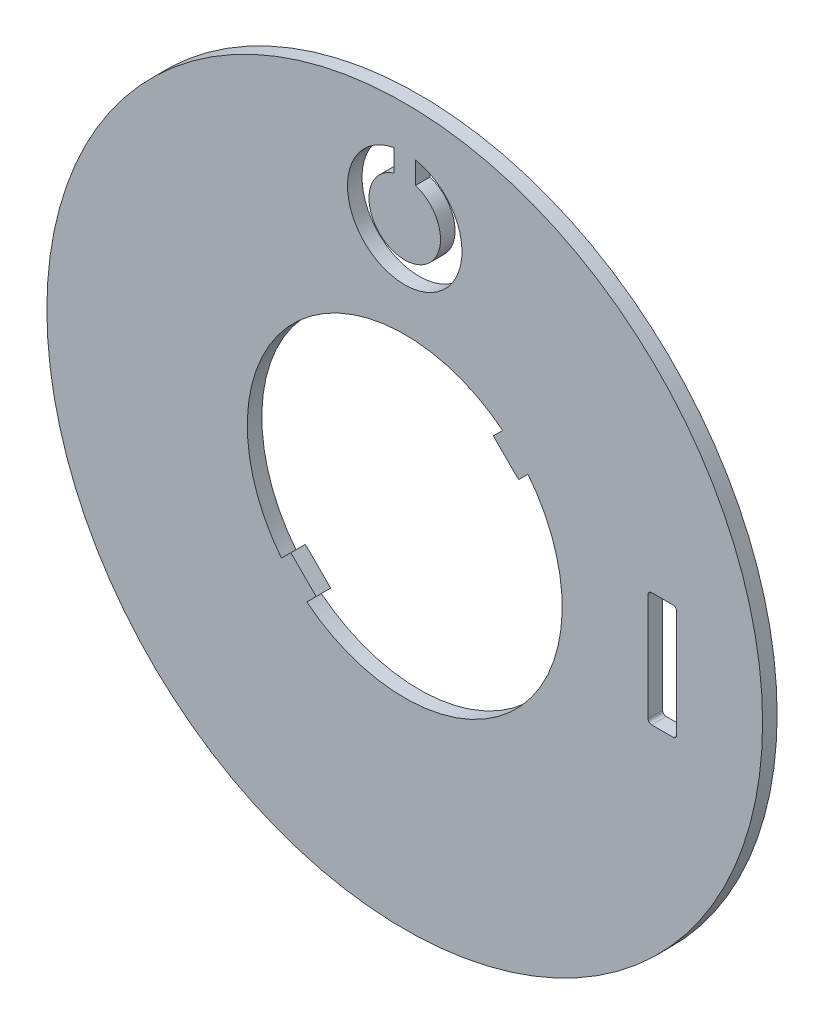
SolidWorks part; units mm, degrees
material "6061-T4 (SS)"
ref_plane "Front Plane" through (0, 0, 0) normal (0, 0, 1) x (1, 0, 0)
ref_plane "Top Plane" through (0, 0, 0) normal (0, 1, 0) x (1, 0, 0)
ref_plane "Right Plane" through (0, 0, 0) normal (1, 0, 0) x (0, 0, -1)
sketch "Sketch1" plane through (0, 0, 0) normal (0, 0, 1) x (1, 0, 0)
  line L4 (115.6621, 68.6943) -> (113.8943, 70.4621)
  line L5 (114.955, 67.9872) -> (115.6621, 68.6943)
  line L6 (113.1872, 69.755) -> (114.955, 67.9872)
  line L7 (113.8943, 70.4621) -> (113.1872, 69.755)
  line L8 (115.6621, 68.6943) -> (113.8943, 70.4621)
  line L9 (114.955, 67.9872) -> (115.6621, 68.6943)
  line L10 (113.1872, 69.755) -> (114.955, 67.9872)
  line L11 (113.8943, 70.4621) -> (113.1872, 69.755)
  line L12 (-125.42, 34.7291) -> (-68.36, 34.7291)
  line L13 (-68.36, 34.7291) -> (-68.36, 51.7891)
  line L14 (-68.36, 51.7891) -> (-125.42, 51.7891)
  line L15 (-125.42, 51.7891) -> (-125.42, 34.7291)
  line L16 (-125.42, 34.7291) -> (-68.36, 34.7291)
  line L17 (-68.36, 34.7291) -> (-68.36, 51.7891)
  line L18 (-68.36, 51.7891) -> (-125.42, 51.7891)
  line L19 (-125.42, 51.7891) -> (-125.42, 34.7291)
  line L20 (100.1057, 53.1379) -> (100.8128, 53.845)
  line L21 (100.8128, 53.845) -> (99.045, 55.6128)
  line L22 (99.045, 55.6128) -> (98.3379, 54.9057)
  line L23 (98.3379, 54.9057) -> (100.1057, 53.1379)
  line L24 (100.1057, 53.1379) -> (100.8128, 53.845)
  line L25 (100.8128, 53.845) -> (99.045, 55.6128)
  line L26 (99.045, 55.6128) -> (98.3379, 54.9057)
  line L27 (98.3379, 54.9057) -> (100.1057, 53.1379)
  line L28 (45.6621, 68.6943) -> (43.8943, 70.4621)
  line L29 (44.955, 67.9872) -> (45.6621, 68.6943)
  line L30 (43.1872, 69.755) -> (44.955, 67.9872)
  line L31 (43.8943, 70.4621) -> (43.1872, 69.755)
  line L32 (45.6621, 68.6943) -> (43.8943, 70.4621)
  line L33 (44.955, 67.9872) -> (45.6621, 68.6943)
  line L34 (43.1872, 69.755) -> (44.955, 67.9872)
  line L35 (43.8943, 70.4621) -> (43.1872, 69.755)
  line L36 (30.1057, 53.1379) -> (30.8128, 53.845)
  line L37 (28.3379, 54.9057) -> (30.1057, 53.1379)
  line L38 (29.045, 55.6128) -> (28.3379, 54.9057)
  line L39 (30.8128, 53.845) -> (29.045, 55.6128)
  line L40 (30.1057, 53.1379) -> (30.8128, 53.845)
  line L41 (28.3379, 54.9057) -> (30.1057, 53.1379)
  line L42 (29.045, 55.6128) -> (28.3379, 54.9057)
  line L43 (30.8128, 53.845) -> (29.045, 55.6128)
  circle A3 centre (-76.89, 43.2591) radius 6.03
  circle A5 centre (-76.89, 43.2591) radius 6.03
  circle A7 centre (-96.89, 43.2591) radius 6.03
  circle A9 centre (-96.89, 43.2591) radius 6.03
  circle A11 centre (-116.89, 43.2591) radius 6.03
  circle A13 centre (-116.89, 43.2591) radius 6.03
  circle A28 centre (37, 61.8) radius 25
  circle A29 centre (37, 61.8) radius 25
  circle A30 centre (107, 61.8) radius 25
  circle A31 centre (107, 61.8) radius 25
  circle A32 centre (37, 61.8) radius 11
  circle A33 centre (37, 61.8) radius 11
  circle A34 centre (107, 61.8) radius 11
  circle A35 centre (107, 61.8) radius 11
  dimension "D1" = 0
  dimension "D2" = 0
  dimension "D3" = 0
  dimension "D4" = 0
  dimension "D5" = 0
  dimension "D6" = 0
  dimension "D7" = 0
  dimension "D8" = 0
  dimension "D9" = 0
  dimension "D10" = 0
  dimension "D11" = 0
  dimension "D12" = 0
extrude "Boss-Extrude1" add sketch "Sketch1" along normal blind 1.016 contours A29 A33 L35 L32 L33 L40 L41 L42
sketch "Sketch2" plane through (0, 0, 0) normal (0, 0, 1) x (1, 0, 0)
  line L0 (37, 72.8) -> (37, 86.8) construction
  line L1 (36.25, 82.1848) -> (36.25, 83.7291)
  line L2 (37.75, 83.7291) -> (37.75, 82.1848)
  line L3 (37.75, 82.957) -> (36.25, 82.957) construction
  line L4 (48, 61.8) -> (62, 61.8) construction
  line L8 (54.25, 57.8) -> (55.75, 57.8)
  line L9 (54, 58.05) -> (54, 65.55)
  line L10 (54.25, 65.8) -> (55.75, 65.8)
  line L11 (56, 58.05) -> (56, 65.55)
  line L12 (54, 57.8) -> (56, 65.8) construction
  line L13 (54, 65.8) -> (56, 57.8) construction
  arc A4 (36.25, 83.7291) -> (37.75, 83.7291) centre (37, 79.8) ccw
  arc A5 (36.25, 82.1848) -> (37.75, 82.1848) centre (37, 79.8) ccw
  arc A7 (55.75, 65.8) -> (56, 65.55) centre (55.75, 65.55) cw
  arc A8 (54, 65.55) -> (54.25, 65.8) centre (54.25, 65.55) cw
  arc A9 (54.25, 57.8) -> (54, 58.05) centre (54.25, 58.05) cw
  arc A10 (55.75, 57.8) -> (56, 58.05) centre (55.75, 58.05) ccw
  circle A11 centre (37, 61.8) radius 11 construction
  circle A12 centre (37, 61.8) radius 11
  circle A13 centre (37, 61.8) radius 25 construction
  circle A14 centre (37, 61.8) radius 25
  point P3 (37, 79.8)
  point P5 (55, 61.8)
  dimension "D2" = 1.5
  dimension "D3" = 4
  dimension "D7" = 0.25
  dimension "D4" = 2
  dimension "D5" = 8
  dimension "D6" = 1.5
extrude "Cut-Extrude1" cut sketch "Sketch2" along normal through all contours A5 L1 A4 L2 | L8 A10 L11 A7 L10 A8 L9 A9
